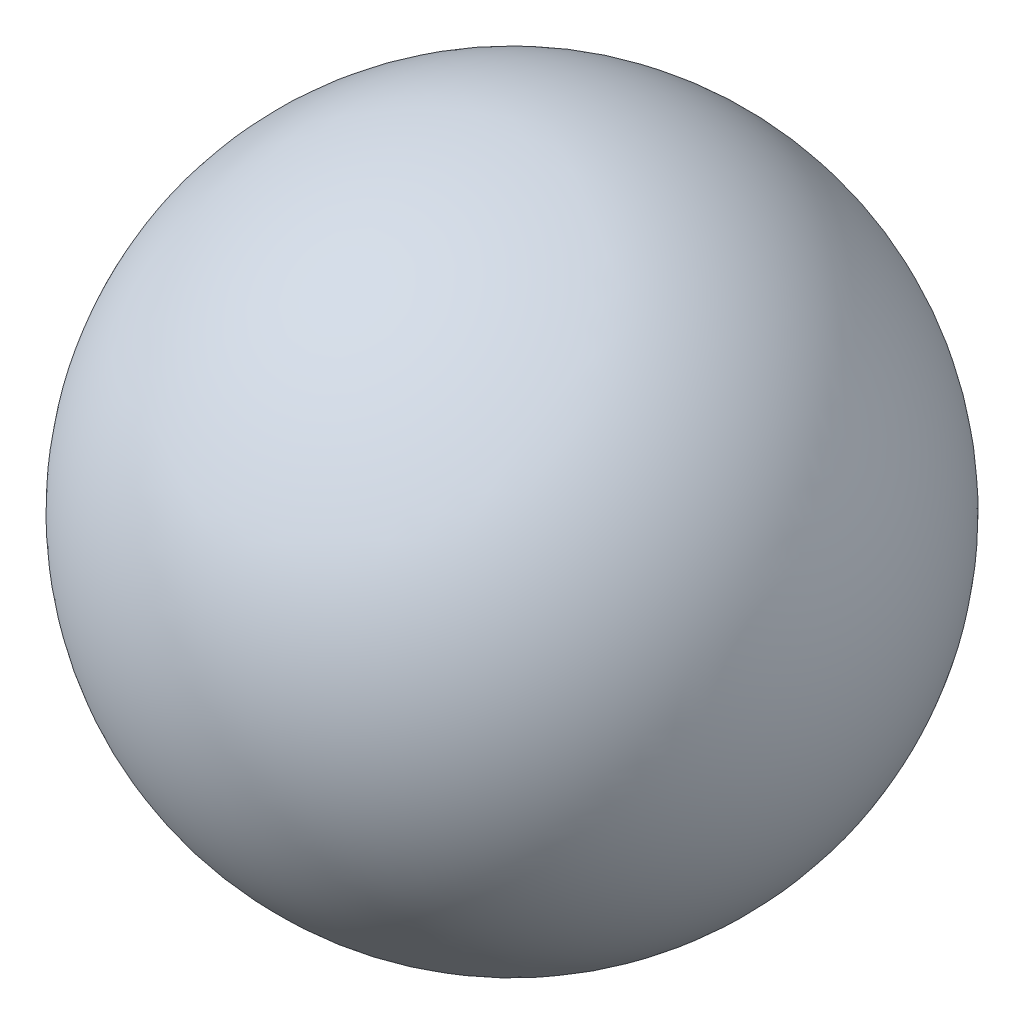
SolidWorks part; units mm, degrees
material "Polyurethane Foam Flexible"
ref_plane "Front Plane" through (0, 0, 0) normal (0, 0, 1) x (1, 0, 0)
ref_plane "Top Plane" through (0, 0, 0) normal (0, 1, 0) x (1, 0, 0)
ref_plane "Right Plane" through (0, 0, 0) normal (1, 0, 0) x (0, 0, -1)
sketch "Sketch1" plane through (0, 0, 0) normal (0, 1, 0) x (1, 0, 0)
  line L0 (-21, 0) -> (21, 0)
  arc A0 (-21, 0) -> (21, 0) centre (0, 0) cw
  dimension "D1" = 21
revolve "Revolve1" add sketch "Sketch1" angle 360 about L0
